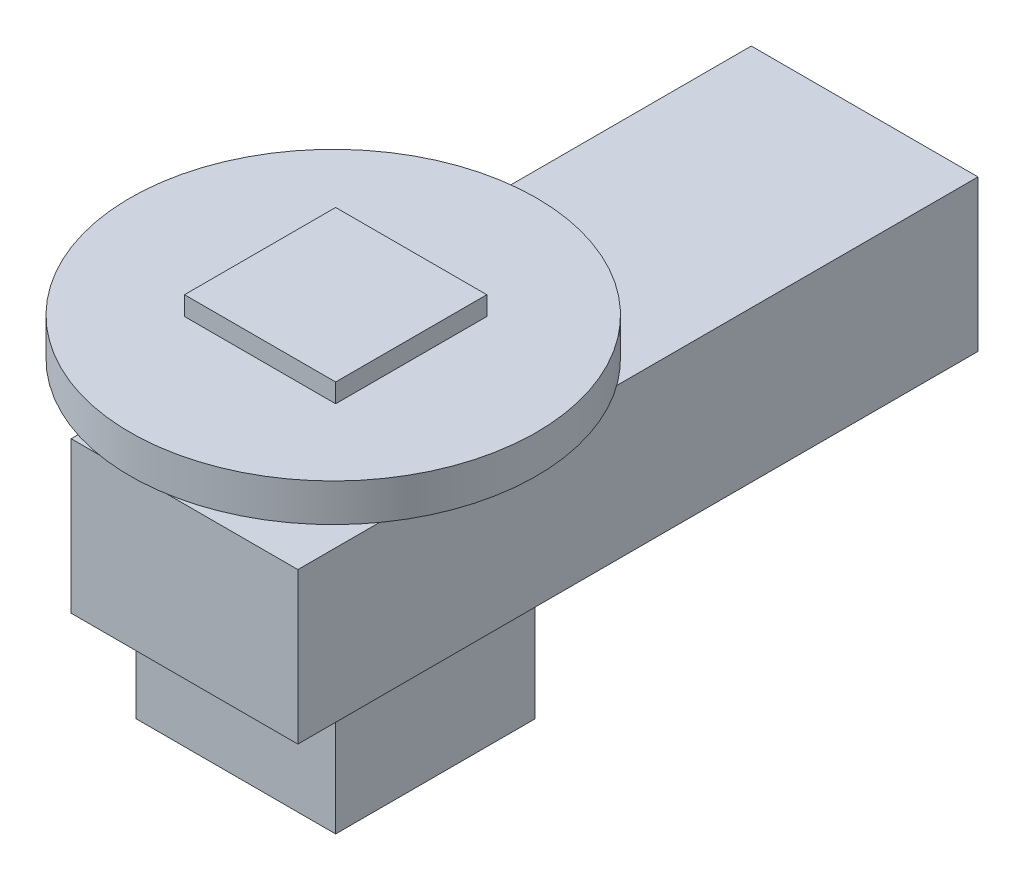
SolidWorks part; units mm, degrees
ref_plane "Front Plane" through (0, 0, 0) normal (0, 0, 1) x (1, 0, 0)
ref_plane "Top Plane" through (0, 0, 0) normal (0, 1, 0) x (1, 0, 0)
ref_plane "Right Plane" through (0, 0, 0) normal (1, 0, 0) x (0, 0, -1)
sketch "Sketch1" plane through (0, 0, 0) normal (0, 0, 1) x (1, 0, 0)
  line L1 (0, 0) -> (-38.1, 0)
  line L2 (0, 0) -> (0, 25.4)
  line L3 (0, 25.4) -> (-38.1, 25.4)
  line L4 (-38.1, 0) -> (-38.1, 25.4)
  dimension "D1" = 25.4
  dimension "D2" = 38.1
extrude "Boss-Extrude1" add sketch "Sketch1" along normal blind 114.3
sketch "Sketch2" plane through (0, 25.4, 0) normal (0, 1, 0) x (1, 0, 0)
  line L0 (0, -114.3) -> (-38.1, -114.3) construction
  circle A0 centre (-19.05, -88.9) radius 6.35
  point P4 (-19.05, -114.3)
  dimension "D2" = 12.7
  dimension "D1" = 25.4
sketch "Sketch3" plane through (0, 0, 0) normal (0, -1, 0) x (1, 0, 0)
  line L1 (-2.286, 105.664) -> (-35.814, 105.664)
  line L2 (-2.286, 105.664) -> (-2.286, 72.136)
  line L3 (-2.286, 72.136) -> (-35.814, 72.136)
  line L4 (-35.814, 105.664) -> (-35.814, 72.136)
  line L6 (-19.05, 105.664) -> (-19.05, 72.136) construction
  line L7 (-38.1, 114.3) -> (0, 114.3) construction
  point P8 (-19.05, 114.3)
  point P9 (-19.05, 88.9)
  dimension "D1" = 33.528
extrude "Boss-Extrude2" add sketch "Sketch3" along normal blind 18.542
extrude "Boss-Extrude3" add sketch "Sketch2" along normal blind 17.78 contours A0
sketch "Sketch4" plane through (0, 43.18, 0) normal (0, 1, 0) x (1, 0, 0)
  line L1 (-31.75, -101.6) -> (-6.35, -101.6)
  line L2 (-31.75, -101.6) -> (-31.75, -76.2)
  line L3 (-31.75, -76.2) -> (-6.35, -76.2)
  line L4 (-6.35, -101.6) -> (-6.35, -76.2)
  line L5 (-31.75, -101.6) -> (-6.35, -76.2) construction
  line L6 (-31.75, -76.2) -> (-6.35, -101.6) construction
  point P0 (-19.05, -88.9)
  dimension "D1" = 25.4
extrude "Boss-Extrude4" add sketch "Sketch4" against normal blind 6.35
sketch "Sketch5" plane through (0, 36.83, 0) normal (0, -1, 0) x (1, 0, 0)
  circle A0 centre (-19.4507, 88.9) radius 34.1376
  dimension "D1" = 68.2752
extrude "Boss-Extrude5" add sketch "Sketch5" along normal mid plane 6.35
ref_plane "Plane1" through (0, 36.83, 0) normal (0, 1, 0) x (1, 0, 0)
ref_plane "Plane2" through (0, 0, 88.9) normal (0, 0, 1) x (1, 0, 0)
